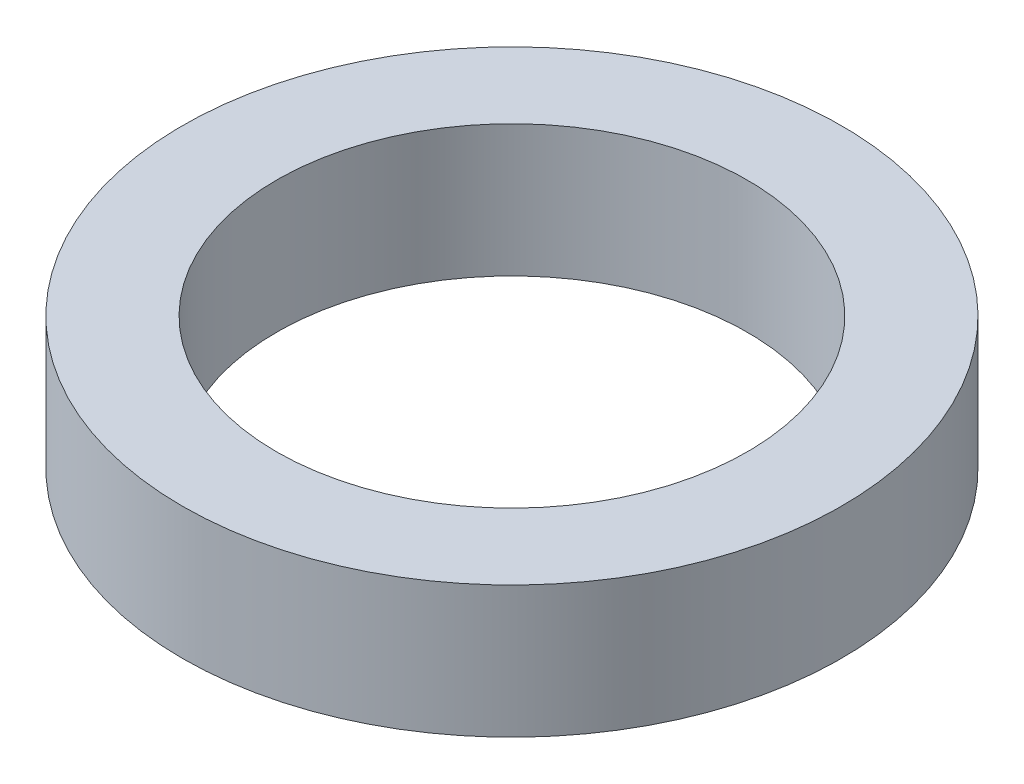
SolidWorks part; units mm, degrees
material "AISI 304"
ref_plane "前视基准面" through (0, 0, 0) normal (0, 0, 1) x (1, 0, 0)
ref_plane "上视基准面" through (0, 0, 0) normal (0, 1, 0) x (1, 0, 0)
ref_plane "右视基准面" through (0, 0, 0) normal (1, 0, 0) x (0, 0, -1)
other "Configuration Table"
sketch "草图1" plane through (0, 0, 0) normal (0, 1, 0) x (1, 0, 0)
  circle A0 centre (0, 0) radius 25
  circle A1 centre (0, 0) radius 35
  dimension "D1" = 50
  dimension "D2" = 70
extrude "凸台-拉伸1" add sketch "草图1" along normal blind 14
